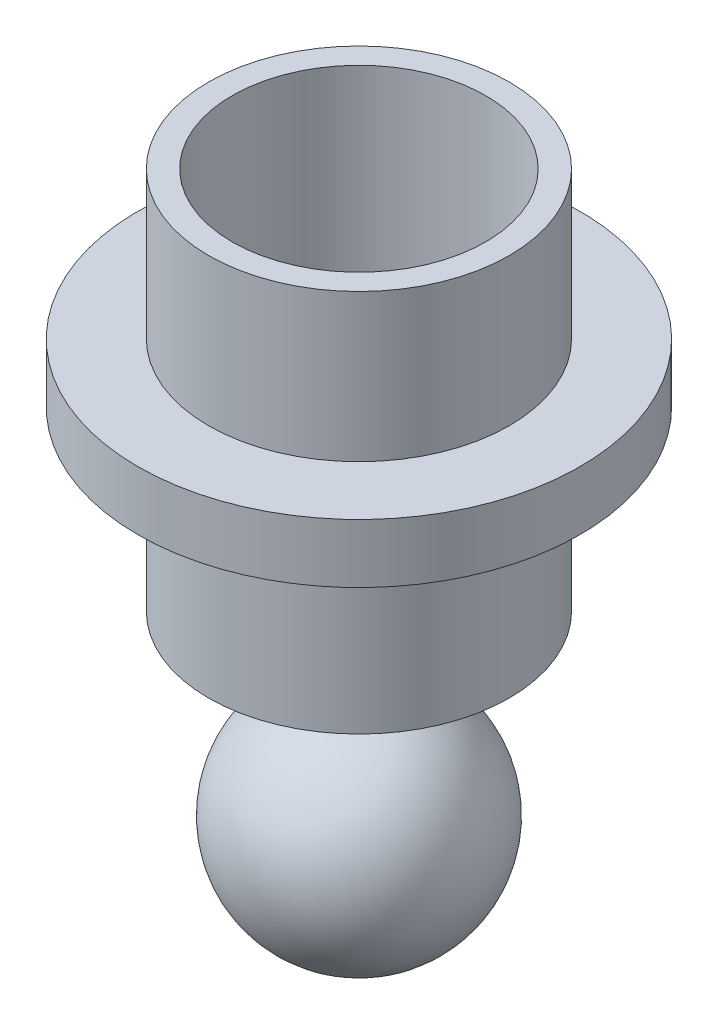
SolidWorks part; units mm, degrees
ref_plane "Front Plane" through (0, 0, 0) normal (0, 0, 1) x (1, 0, 0)
ref_plane "Top Plane" through (0, 0, 0) normal (0, 1, 0) x (1, 0, 0)
ref_plane "Right Plane" through (0, 0, 0) normal (1, 0, 0) x (0, 0, -1)
sketch "Sketch2" plane through (0, 0, 0) normal (0, 1, 0) x (1, 0, 0)
  circle A0 centre (0, 0) radius 5.1
  dimension "D1" = 10.2
extrude "Boss-Extrude1" add sketch "Sketch2" along normal blind 1
sketch "Sketch3" plane through (0, 1, 0) normal (0, 1, 0) x (1, 0, 0)
  circle A0 centre (0, 0) radius 5.1
  circle A1 centre (0, 0) radius 4.3
  dimension "D1" = 10.2
  dimension "D2" = 8.6
extrude "Boss-Extrude2" add sketch "Sketch3" along normal blind 12
sketch "Sketch6" plane through (0, 1, 0) normal (0, 1, 0) x (1, 0, 0)
  line L0 (0, 0) -> (0, 3.3)
  line L1 (0, 0) -> (-0.8541, 3.1876) construction
  line L2 (0, 0) -> (0.8541, 3.1876) construction
  line L3 (0.8541, 3.1876) -> (0.647, 2.4148)
  line L4 (-0.8541, 3.1876) -> (-0.647, 2.4148)
  line L5 (3.1876, 0.8541) -> (2.4148, 0.647)
  line L6 (2.3335, 2.3335) -> (1.7678, 1.7678)
  line L7 (2.3335, -2.3335) -> (1.7678, -1.7678)
  line L8 (3.1876, -0.8541) -> (2.4148, -0.647)
  line L9 (-0.8541, -3.1876) -> (-0.647, -2.4148)
  line L10 (0.8541, -3.1876) -> (0.647, -2.4148)
  line L11 (-3.1876, -0.8541) -> (-2.4148, -0.647)
  line L12 (-2.3335, -2.3335) -> (-1.7678, -1.7678)
  line L13 (-2.3335, 2.3335) -> (-1.7678, 1.7678)
  line L14 (-3.1876, 0.8541) -> (-2.4148, 0.647)
  arc A0 (0.8541, 3.1876) -> (-0.8541, 3.1876) centre (0, 0) ccw
  arc A1 (0.647, 2.4148) -> (-0.647, 2.4148) centre (0, 0) ccw
  arc A2 (3.1876, 0.8541) -> (2.3335, 2.3335) centre (0, 0) ccw
  arc A3 (2.4148, 0.647) -> (1.7678, 1.7678) centre (0, 0) ccw
  arc A4 (2.3335, -2.3335) -> (3.1876, -0.8541) centre (0, 0) ccw
  arc A5 (1.7678, -1.7678) -> (2.4148, -0.647) centre (0, 0) ccw
  arc A6 (-0.8541, -3.1876) -> (0.8541, -3.1876) centre (0, 0) ccw
  arc A7 (-0.647, -2.4148) -> (0.647, -2.4148) centre (0, 0) ccw
  arc A8 (-3.1876, -0.8541) -> (-2.3335, -2.3335) centre (0, 0) ccw
  arc A9 (-2.4148, -0.647) -> (-1.7678, -1.7678) centre (0, 0) ccw
  arc A10 (-2.3335, 2.3335) -> (-3.1876, 0.8541) centre (0, 0) ccw
  arc A11 (-1.7678, 1.7678) -> (-2.4148, 0.647) centre (0, 0) ccw
  point P29 (0, 0)
  dimension "D1" = 6.6
  dimension "D2" = 5
  dimension "D3" = 15
  dimension "D4" = 15
  dimension "D5" = 6
extrude "Cut-Extrude2" cut sketch "Sketch6" against normal blind 1 contours A11 L13 A10 L14 | A3 L5 A2 L6 | A5 L7 A4 L8 | A7 L9 A6 L10 | A9 L11 A8 L12 | A1 L4 A0 L3
ref_plane "Plane2" through (0, 6, 0) normal (0, 1, 0) x (1, 0, 0)
sketch "Sketch7" plane through (0, 6, 0) normal (0, 1, 0) x (1, 0, 0)
  circle A0 centre (0, 0) radius 7.5
  circle A1 centre (0, 0) radius 5.1
  dimension "D1" = 15
  dimension "D2" = 10.2
extrude "Boss-Extrude4" add sketch "Sketch7" along normal blind 2
sketch "Sketch10" plane through (0, 0, 0) normal (1, 0, 0) x (0, 0, -1)
  line L0 (0, 0) -> (0, -6) construction
  line L1 (1.5, 0) -> (1.5, -2.4)
  line L2 (-5.1, 0) -> (5.1, 0) construction
  line L3 (-1.5, -2.4) -> (-1.5, 0)
  line L4 (0, 0) -> (-1.5, 0)
  line L5 (0, 0) -> (1.5, 0)
  line L6 (0, -2.1) -> (0, -9.9)
  circle A0 centre (0, -6) radius 3.9
  dimension "D2" = 7.8
  dimension "D1" = 6
  dimension "D3" = 3
revolve "Revolve1" add sketch "Sketch10" angle 360 about L6
